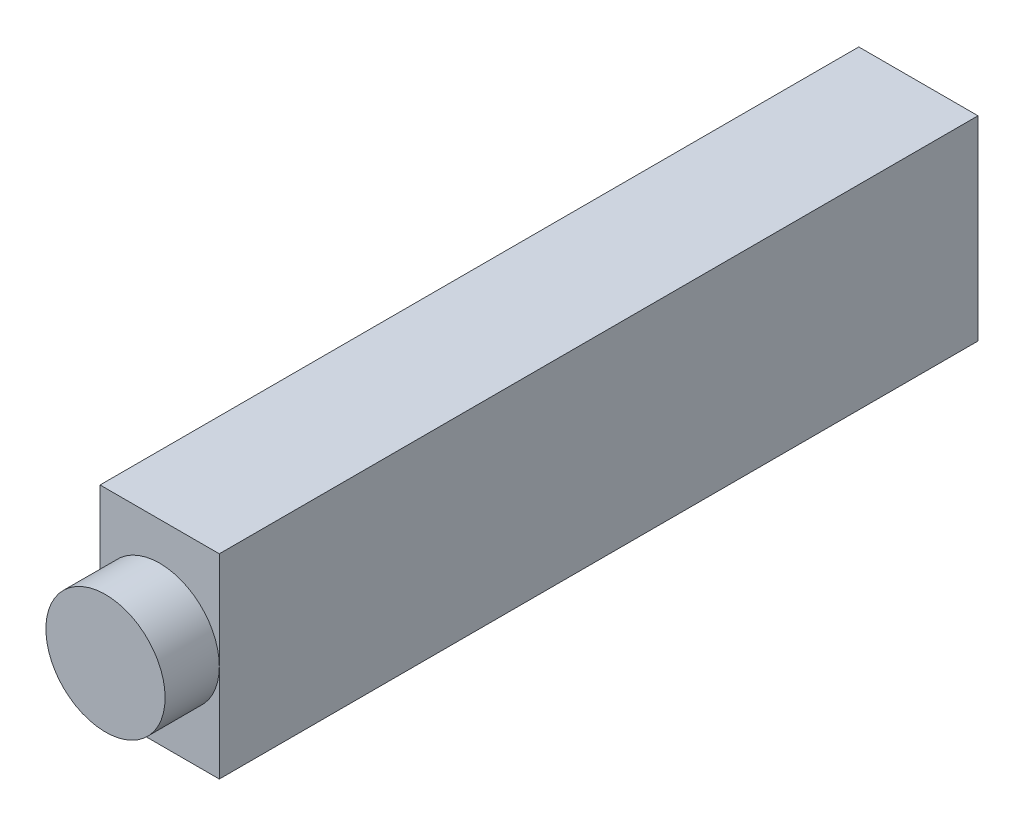
SolidWorks part; units mm, degrees
ref_plane "Front Plane" through (0, 0, 0) normal (0, 0, 1) x (1, 0, 0)
ref_plane "Top Plane" through (0, 0, 0) normal (0, 1, 0) x (1, 0, 0)
ref_plane "Right Plane" through (0, 0, 0) normal (1, 0, 0) x (0, 0, -1)
sketch "Sketch1" plane through (0, 0, 0) normal (0, 0, 1) x (1, 0, 0)
  circle A0 centre (0, 0) radius 11
  dimension "D1" = 22
extrude "Boss-Extrude1" add sketch "Sketch1" along normal blind 10
sketch "Sketch2" plane through (0, 0, 0) normal (0, 0, -1) x (-1, 0, 0)
  circle A0 centre (0, 0) radius 20
  dimension "D1" = 40
sketch "Sketch3" plane through (0, 0, 0) normal (0, 0, -1) x (-1, 0, 0)
  line L1 (11, 18) -> (-11, 18)
  line L2 (11, 18) -> (11, -18)
  line L3 (11, -18) -> (-11, -18)
  line L4 (-11, 18) -> (-11, -18)
  line L5 (11, 18) -> (-11, -18) construction
  line L6 (11, -18) -> (-11, 18) construction
  point P0 (0, 0)
  dimension "D1" = 22
  dimension "D2" = 36
extrude "Boss-Extrude2" add sketch "Sketch3" along normal blind 140
sketch "Sketch4" plane through (11, 0, 0) normal (1, 0, 0) x (0, 0, -1)
  line L0 (140, -18) -> (117.5, -18) construction
  line L1 (140, -18) -> (0, -18) construction
  line L2 (117.5, -18) -> (117.5, -5.5) construction
  circle A0 centre (117.5, -5.5) radius 7.125
  dimension "D3" = 14.25
  dimension "D1" = 22.5
  dimension "D2" = 12.5
